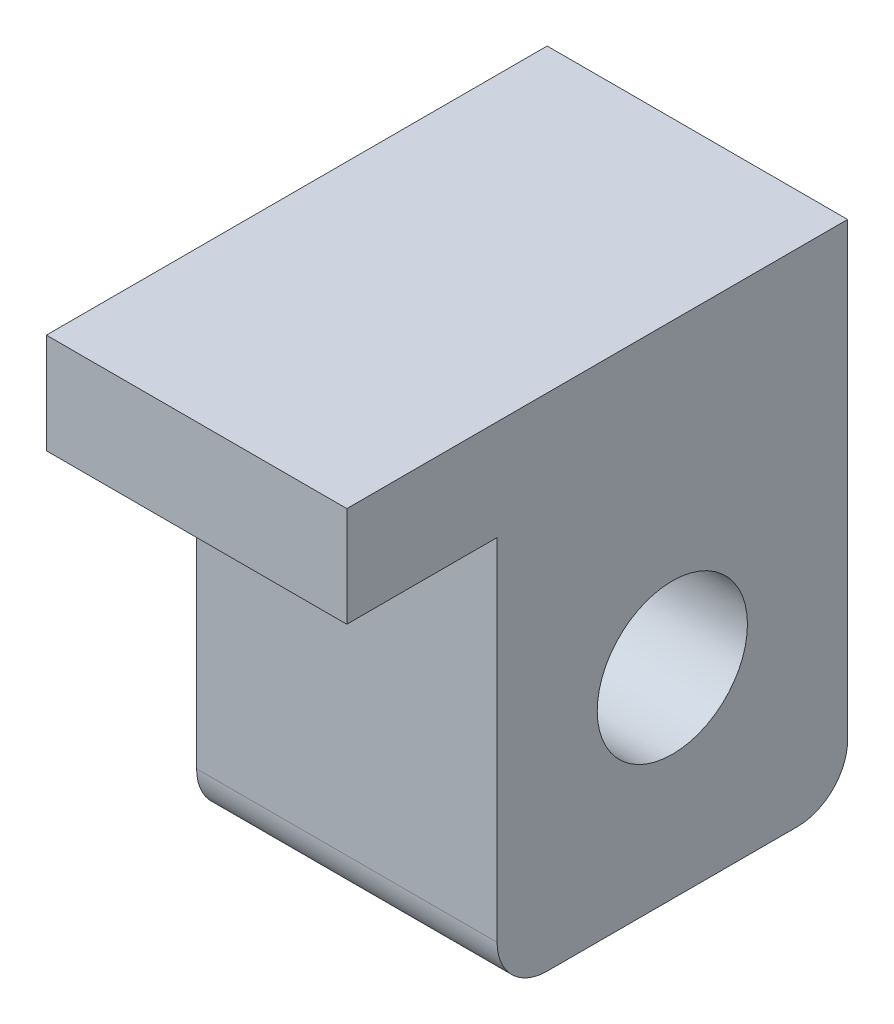
SolidWorks part; units mm, degrees
ref_plane "前视基准面" through (0, 0, 0) normal (0, 0, 1) x (1, 0, 0)
ref_plane "上视基准面" through (0, 0, 0) normal (0, 1, 0) x (1, 0, 0)
ref_plane "右视基准面" through (0, 0, 0) normal (1, 0, 0) x (0, 0, -1)
other "Configuration Table"
sketch "草图2" plane through (0, 0, 0) normal (1, 0, 0) x (0, 0, -1)
  line L1 (-17.5, -25) -> (17.5, -25)
  line L2 (-17.5, -25) -> (-17.5, 25)
  line L3 (-17.5, 25) -> (17.5, 25)
  line L4 (17.5, -25) -> (17.5, 25)
  line L5 (-17.5, -25) -> (17.5, 25) construction
  line L6 (-17.5, 25) -> (17.5, -25) construction
  point P0 (0, 0)
  dimension "D1" = 35
  dimension "D2" = 50
extrude "凸台-拉伸1" add sketch "草图2" along normal blind 30
sketch "草图3" plane through (30, 0, 0) normal (1, 0, 0) x (0, 0, -1)
  line L0 (-17.5, -25) -> (17.5, -25) construction
  line L1 (17.5, -25) -> (17.5, 25) construction
  circle A0 centre (0, -5) radius 7.5
  dimension "D1" = 15
  dimension "D2" = 20
  dimension "D3" = 17.5
extrude "切除-拉伸1" cut sketch "草图3" against normal through all and the other way through all
fillet "圆角1" radius 5 1 edges at (15, -25, -17.5)
fillet "圆角2" radius 5 1 edges at (15, -25, 17.5)
sketch "草图4" plane through (0, 0, 0) normal (-1, 0, 0) x (0, 0, 1)
  circle A1 centre (11.3137, 6.3137) radius 2.75
  circle A2 centre (11.3137, 6.3137) radius 2.75
  circle A5 centre (-11.3137, 6.3137) radius 2.75
  circle A6 centre (-11.3137, 6.3137) radius 2.75
  circle A7 centre (-11.3137, -16.3137) radius 2.75
  circle A8 centre (-11.3137, -16.3137) radius 2.75
  circle A11 centre (11.3137, -16.3137) radius 2.75
  circle A12 centre (11.3137, -16.3137) radius 2.75
  dimension "D1" = 0
  dimension "D3" = 0
  dimension "D4" = 0
  dimension "D6" = 0
extrude "切除-拉伸2" cut sketch "草图4" against normal blind 20
sketch "草图5" plane through (0, 25, 0) normal (0, 1, 0) x (1, 0, 0)
  line L0 (30, 17.5) -> (30, -17.5) construction
  line L1 (30, -32.5) -> (0, -32.5)
  line L2 (30, -32.5) -> (30, -17.5)
  line L3 (30, -17.5) -> (0, -17.5)
  line L4 (0, -32.5) -> (0, -17.5)
  dimension "D1" = 15
extrude "凸台-拉伸2" add sketch "草图5" against normal blind 10
